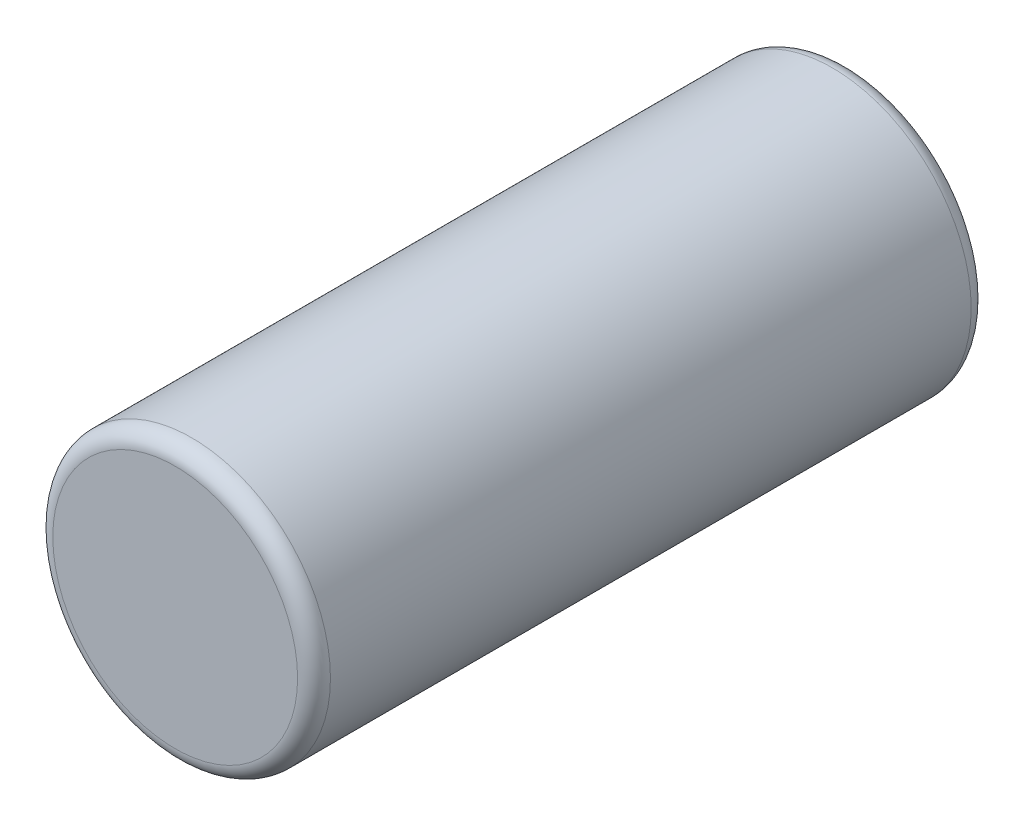
SolidWorks part; units mm, degrees
ref_plane "Ön Düzlem" through (0, 0, 0) normal (0, 0, 1) x (1, 0, 0)
ref_plane "Üst Düzlem" through (0, 0, 0) normal (0, 1, 0) x (1, 0, 0)
ref_plane "Sağ Düzlem" through (0, 0, 0) normal (1, 0, 0) x (0, 0, -1)
sketch "Çizim2" plane through (0, 0, 0) normal (0, 0, 1) x (1, 0, 0)
  circle A0 centre (0, 0) radius 16.9
extrude "Yükseklik-Ekstrüzyon1" add sketch "Çizim2" along normal mid plane 82
fillet "Radyus1" radius 2 2 edges at (16.9, 0, -41) (16.9, 0, 41)
